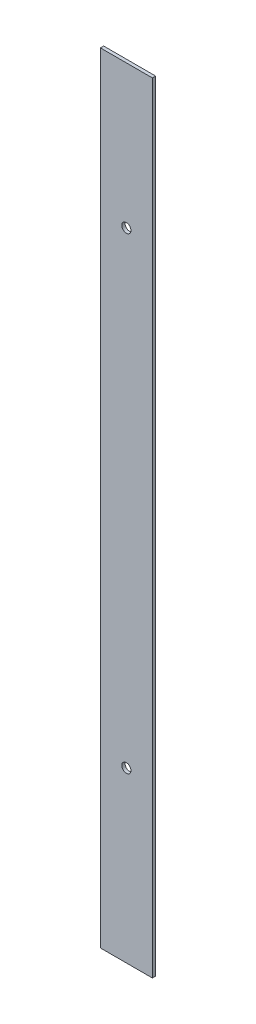
SolidWorks part; units mm, degrees
material "ABS PC"
ref_plane "Front Plane" through (0, 0, 0) normal (0, 0, 1) x (1, 0, 0)
ref_plane "Top Plane" through (0, 0, 0) normal (0, 1, 0) x (1, 0, 0)
ref_plane "Right Plane" through (0, 0, 0) normal (1, 0, 0) x (0, 0, -1)
sketch "Sketch1" plane through (0, 0, 0) normal (0, 0, 1) x (1, 0, 0)
  line L1 (0, 0) -> (25.4, 0)
  line L2 (0, 0) -> (0, 381)
  line L3 (0, 381) -> (25.4, 381)
  line L4 (25.4, 0) -> (25.4, 381)
  circle A0 centre (12.7, 82.55) radius 2.25
  circle A1 centre (12.7, 311.15) radius 2.25
  point P9 (12.7, 0)
  point P10 (0, 0)
  dimension "D4" = 4.5
  dimension "D6" = 4.5
  dimension "D1" = 25.4
  dimension "D2" = 82.55
  dimension "D3" = 228.6
  dimension "D5" = 69.85
extrude "Boss-Extrude1" add sketch "Sketch1" along normal blind 1.5875
